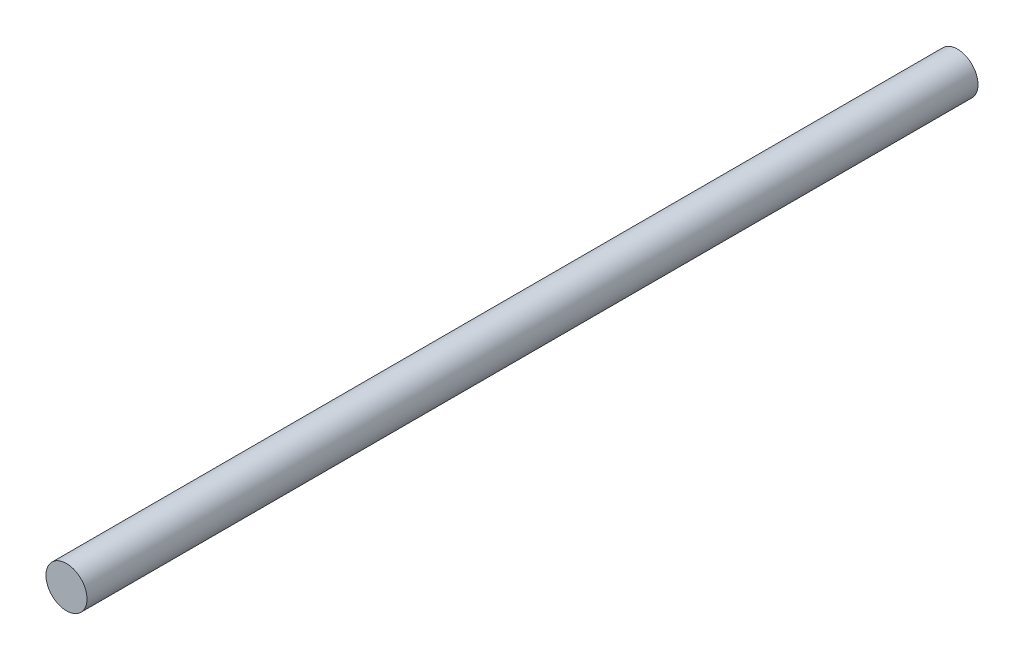
SolidWorks part; units mm, degrees
ref_plane "前视基准面" through (0, 0, 0) normal (0, 0, 1) x (1, 0, 0)
ref_plane "上视基准面" through (0, 0, 0) normal (0, 1, 0) x (1, 0, 0)
ref_plane "右视基准面" through (0, 0, 0) normal (1, 0, 0) x (0, 0, -1)
sketch "草图1" plane through (0, 0, 0) normal (0, 0, 1) x (1, 0, 0)
  circle A1 centre (20, 7) radius 2.8951
extrude "凸台-拉伸1" add sketch "草图1" along normal blind 125.7 contours A1
